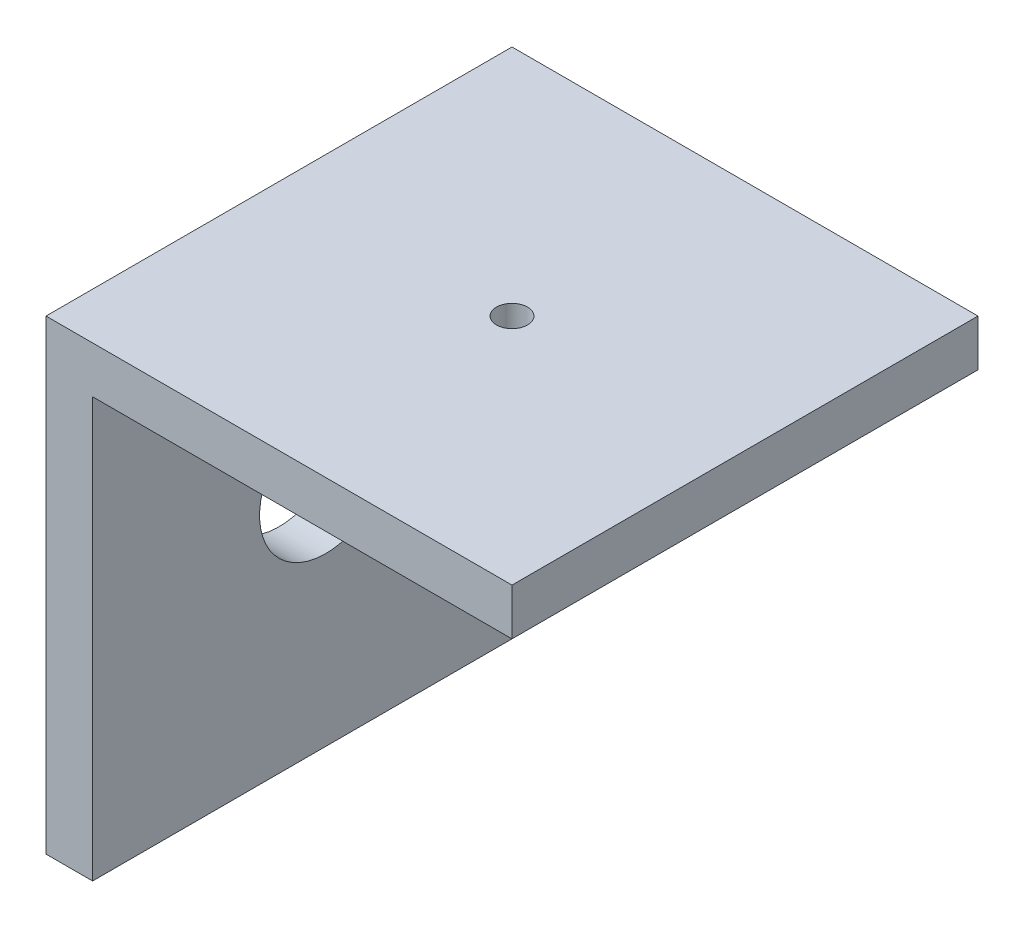
SolidWorks part; units mm, degrees
ref_plane "前视基准面" through (0, 0, 0) normal (0, 0, 1) x (1, 0, 0)
ref_plane "上视基准面" through (0, 0, 0) normal (0, 1, 0) x (1, 0, 0)
ref_plane "右视基准面" through (0, 0, 0) normal (1, 0, 0) x (0, 0, -1)
sketch "草图1" plane through (0, 0, 0) normal (0, 0, 1) x (1, 0, 0)
  line B0 (0, -30) -> (0, 0)
  line B1 (0, 0) -> (30, 0)
  line B2 (3, -30) -> (3, -3)
  line B3 (3, -3) -> (30, -3)
  line B4 (3, -30) -> (0, -30)
  line B5 (30, -3) -> (30, 0)
sketch_block_instance "A$C08FB73BA-1"
sketch_block "A$C08FB73BA"
extrude "凸台-拉伸1" add sketch "草图1" along normal mid plane 30
sketch "草图3" plane through (3, 0, 0) normal (1, 0, 0) x (0, 0, -1)
  line L0 (-15, 0) -> (15, 0) construction
  circle A0 centre (0, -15) radius 4.25
  dimension "D1" = 15
extrude "切除-拉伸1" cut sketch "草图3" against normal through all
sketch "草图4" plane through (0, 0, 0) normal (0, 1, 0) x (1, 0, 0)
  line L0 (0, -15) -> (0, 15) construction
  point P0 (15, 0)
  dimension "D1" = 15
sketch "草图5" plane through (0, 0, 0) normal (0, 1, 0) x (1, 0, 0)
  circle A0 centre (15, 0) radius 1
extrude "切除-拉伸2" cut sketch "草图5" against normal through all
